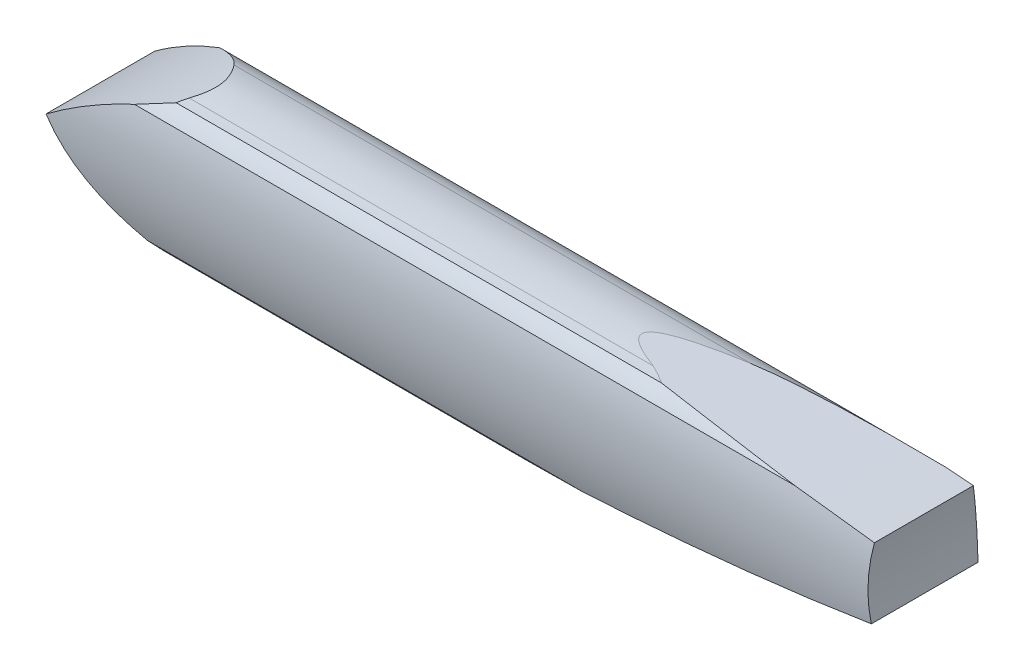
SolidWorks part; units mm, degrees
ref_plane "Front Plane" through (0, 0, 0) normal (0, 0, 1) x (1, 0, 0)
ref_plane "Top Plane" through (0, 0, 0) normal (0, 1, 0) x (1, 0, 0)
ref_plane "Right Plane" through (0, 0, 0) normal (1, 0, 0) x (0, 0, -1)
sketch "Sketch1" plane through (0, 0, 0) normal (0, 0, 1) x (1, 0, 0)
  arc A0 (-192.6294, 0) -> (-73.9915, 55.3217) centre (0.6853, -259.6942) cw
  arc A1 (-73.9915, 55.3217) -> (535.7856, 33.7196) centre (72.3044, -4432.1785) cw
  arc A2 (535.7856, 33.7196) -> (535.7856, -27.0542) centre (821.5032, 3.3327) ccw
  arc A3 (535.7856, -27.0542) -> (-66.5683, -71.6141) centre (20.1225, 2850.0585) cw
  arc A4 (-192.6294, 0) -> (-66.5683, -71.6141) centre (-55.5394, 94.5588) ccw
extrude "Boss-Extrude1" add sketch "Sketch1" along normal blind 100
sketch "Sketch2" plane through (0, 0, 0) normal (1, 0, 0) x (0, 0, -1)
  arc A0 (-65.4472, 54.8304) -> (-92.9565, 40.6004) centre (-65.0756, 20.4068) ccw
  arc A1 (-92.9565, 40.6004) -> (-88.9673, -61.9502) centre (74.239, -4.2486) ccw
  arc A2 (-88.9673, -61.9502) -> (-75.5891, -72.2161) centre (-66.8398, -46.9643) ccw
  arc A3 (-75.5891, -72.2161) -> (-173.3785, -75.4078) centre (-126.0797, -24.9172) cw
  arc A4 (-173.3785, -75.4078) -> (-135.2629, 60.9401) centre (86.0317, -74.4236) cw
  arc A5 (-135.2629, 60.9401) -> (-61.3269, 89.0039) centre (-51.8166, -47.4784) cw
  arc A6 (-61.3269, 89.0039) -> (-65.4472, 54.8304) centre (778.5841, -29.5983) ccw
  point P14 (-92.9565, 40.6004)
  point P15 (-92.9565, -52.6319)
extrude "Cut-Extrude3" cut sketch "Sketch2" against normal through all both and the other way through all
sketch "Sketch3" plane through (0, 0, 0) normal (1, 0, 0) x (0, 0, -1)
  arc A0 (-74.2083, 50.8866) -> (-26.7131, 48.511) centre (-56.0106, -61.2597) cw
  arc A1 (-26.7131, 48.511) -> (-7.715, 36.1895) centre (-36.3575, 12.8336) cw
  arc A2 (-8.6781, -61.6499) -> (-29.5113, -74.3603) centre (-30.579, -49.1815) cw
  arc A3 (-74.2083, 50.8866) -> (12.3195, 83.1167) centre (-99.8212, 251.9147) cw
  arc A4 (12.3195, 83.1167) -> (85.2864, -42.1041) centre (302.1155, 168.113) ccw
  arc A5 (85.2864, -42.1041) -> (-29.5113, -74.3603) centre (9.4865, 7.2561) cw
  arc A6 (-7.715, 36.1895) -> (-8.6781, -61.6499) centre (-213.3664, -10.7106) cw
  point P14 (-74.2083, 50.8866)
extrude "Cut-Extrude5" cut sketch "Sketch3" against normal through all both and the other way through all
